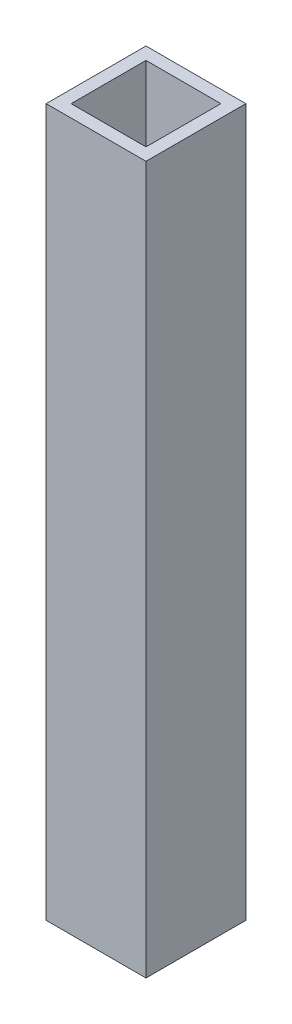
SolidWorks part; units mm, degrees
ref_plane "Alzado" through (0, 0, 0) normal (0, 0, 1) x (1, 0, 0)
ref_plane "Planta" through (0, 0, 0) normal (0, 1, 0) x (1, 0, 0)
ref_plane "Vista lateral" through (0, 0, 0) normal (1, 0, 0) x (0, 0, -1)
sketch "Croquis1" plane through (0, 0, 0) normal (0, 1, 0) x (1, 0, 0)
  line L1 (-9, -9) -> (9, -9)
  line L2 (-9, -9) -> (-9, 9)
  line L3 (-9, 9) -> (9, 9)
  line L4 (9, -9) -> (9, 9)
  line L5 (-9, -9) -> (9, 9) construction
  line L6 (-9, 9) -> (9, -9) construction
  point P0 (0, 0)
  dimension "D1" = 18
  dimension "D2" = 18
extrude "Extruir-Lámina1" add sketch "Croquis1" along normal blind 170 thin
